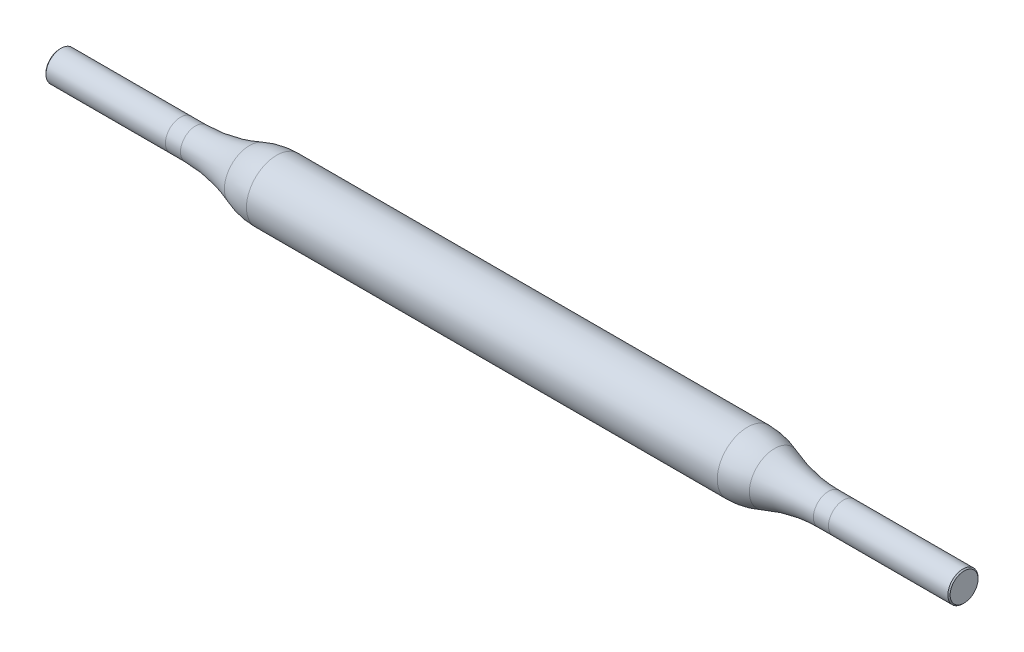
SolidWorks part; units mm, degrees
ref_plane "Front Plane" through (0, 0, 0) normal (0, 0, 1) x (1, 0, 0)
ref_plane "Top Plane" through (0, 0, 0) normal (0, 1, 0) x (1, 0, 0)
ref_plane "Right Plane" through (0, 0, 0) normal (1, 0, 0) x (0, 0, -1)
sketch "Sketch1" plane through (0, 0, 0) normal (0, 1, 0) x (1, 0, 0)
  line L0 (-30, 0) -> (30, 0)
  line L1 (30, 0) -> (30, 1)
  line L2 (-30, 0) -> (-30, 1)
  line L3 (-30, 1) -> (-21, 1)
  line L4 (30, 1) -> (21, 1)
  line L5 (-15.6218, 2) -> (15.6218, 2)
  arc A4 (-21, 1) -> (-17.419, 1.6658) centre (-21, 10.9627) ccw
  arc A5 (17.419, 1.6658) -> (21, 1) centre (21, 10.9627) ccw
  arc A6 (-15.6218, 2) -> (-17.419, 1.6658) centre (-15.6218, -3) ccw
  arc A7 (15.6218, 2) -> (17.419, 1.6658) centre (15.6218, -3) cw
  point P2 (0, 0)
  point P10 (0, 2)
  point P18 (-18, 7.0803)
  dimension "D6" = 5
  dimension "D7" = 5
  dimension "D1" = 60
  dimension "D2" = 1
  dimension "D3" = 9
  dimension "D4" = 2
  dimension "D5" = 3
revolve "Revolve1" add sketch "Sketch1" angle 360 about L0
sketch "Sketch2" plane through (0, 0, 0) normal (0, 0, 1) x (1, 0, 0)
  line L0 (22, 3.7355) -> (22, -4.5656)
  line L1 (-22, 3.7355) -> (-22, -4.0319)
  line L2 (-30, 1) -> (-30, -1) construction
  line L3 (30, -1) -> (30, 1) construction
  dimension "D1" = 8
  dimension "D2" = 8
split line "Split Line1"
chamfer "Chamfer1" distance 0.075 angle 45 2 edges at (-30, 0, 1) (30, 0, 1)
